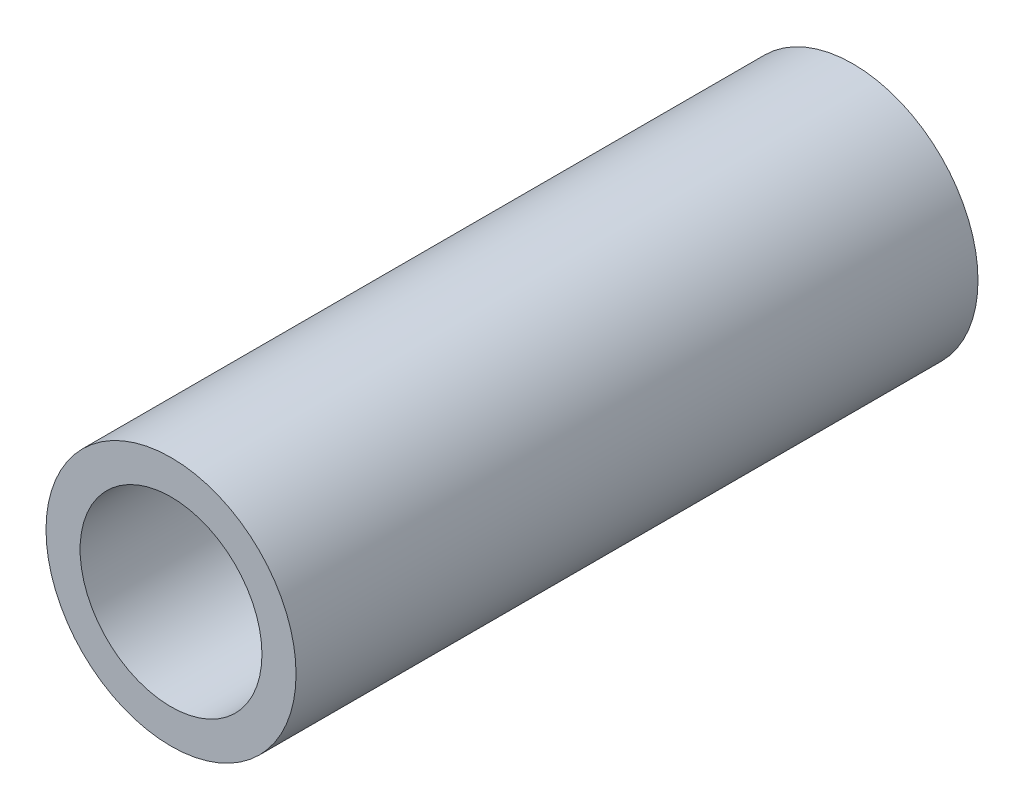
SolidWorks part; units mm, degrees
ref_plane "Alzado" through (0, 0, 0) normal (0, 0, 1) x (1, 0, 0)
ref_plane "Planta" through (0, 0, 0) normal (0, 1, 0) x (1, 0, 0)
ref_plane "Vista lateral" through (0, 0, 0) normal (1, 0, 0) x (0, 0, -1)
sketch "Croquis1" plane through (0, 0, 0) normal (0, 0, 1) x (1, 0, 0)
  circle A0 centre (0, 0) radius 5.5
  dimension "D1" = 11
extrude "Saliente-Extruir1" add sketch "Croquis1" along normal blind 30
sketch "Croquis2" plane through (0, 0, 30) normal (0, 0, 1) x (1, 0, 0)
  circle A0 centre (0, 0) radius 4
extrude "Cortar-Extruir1" cut sketch "Croquis2" against normal blind 30
